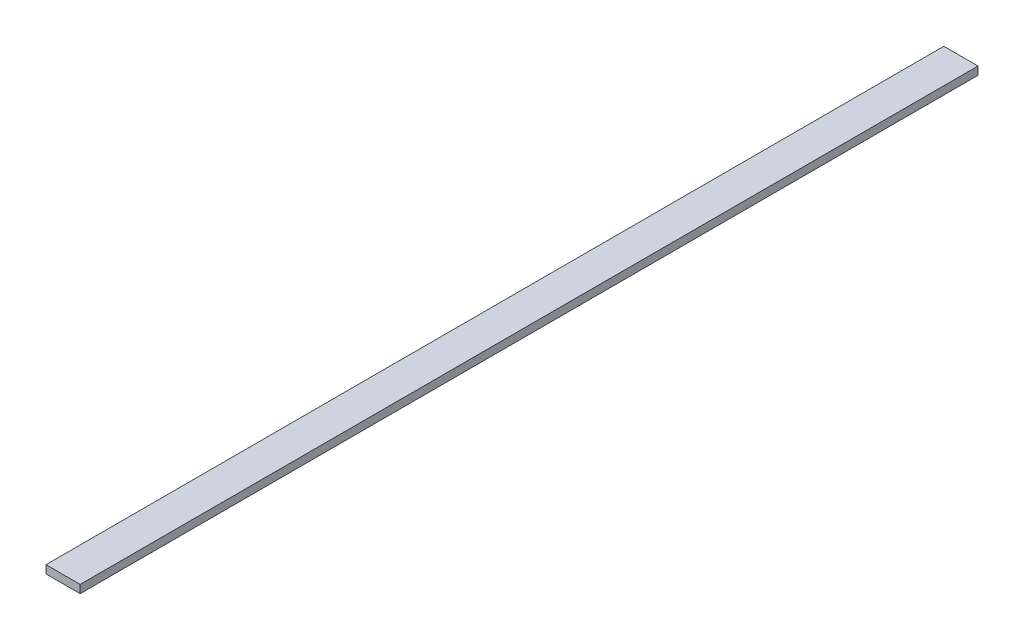
SolidWorks part; units mm, degrees
ref_plane "Alzado" through (0, 0, 0) normal (0, 0, 1) x (1, 0, 0)
ref_plane "Planta" through (0, 0, 0) normal (0, 1, 0) x (1, 0, 0)
ref_plane "Vista lateral" through (0, 0, 0) normal (1, 0, 0) x (0, 0, -1)
sketch "Croquis1" plane through (0, 0, 0) normal (0, 0, 1) x (1, 0, 0)
  line L1 (6.35, -1.5) -> (-6.35, -1.5)
  line L2 (6.35, -1.5) -> (6.35, 1.5)
  line L3 (6.35, 1.5) -> (-6.35, 1.5)
  line L4 (-6.35, -1.5) -> (-6.35, 1.5)
  line L5 (6.35, -1.5) -> (-6.35, 1.5) construction
  line L6 (6.35, 1.5) -> (-6.35, -1.5) construction
  point P0 (0, 0)
  dimension "D1" = 12.7
  dimension "D2" = 3
extrude "Saliente-Extruir1" add sketch "Croquis1" along normal mid plane 334
